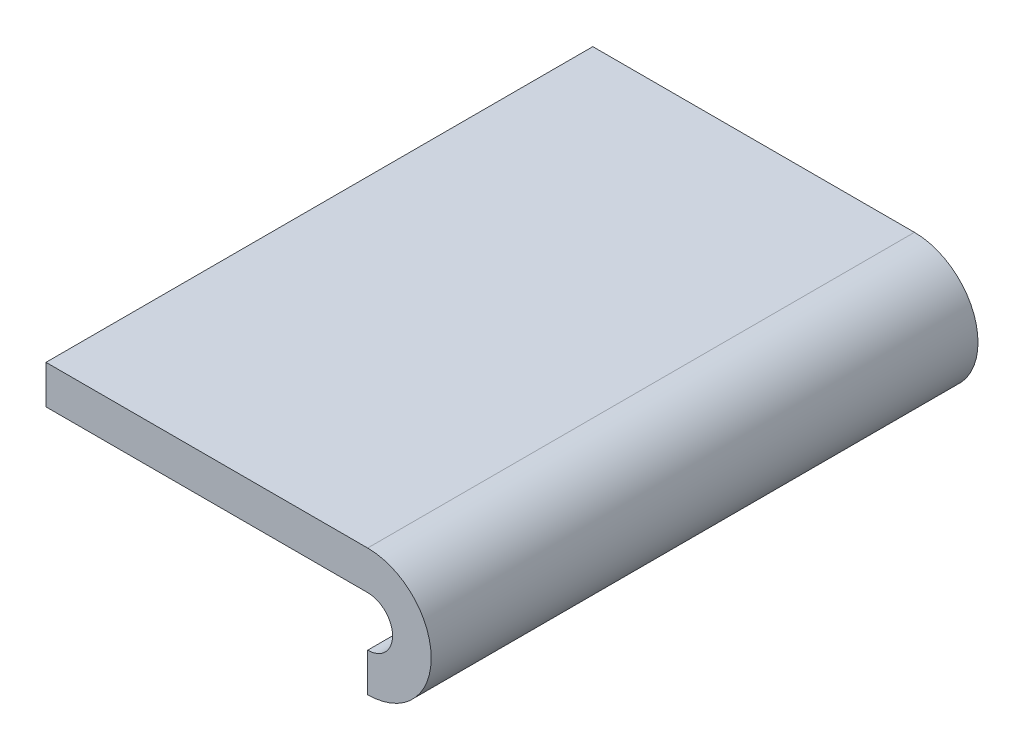
SolidWorks part; units mm, degrees
ref_plane "Front Plane" through (0, 0, 0) normal (0, 0, 1) x (1, 0, 0)
ref_plane "Top Plane" through (0, 0, 0) normal (0, 1, 0) x (1, 0, 0)
ref_plane "Right Plane" through (0, 0, 0) normal (1, 0, 0) x (0, 0, -1)
sketch "Sketch1" plane through (0, 0, 0) normal (0, 0, 1) x (1, 0, 0)
  line L0 (-100, 7.75) -> (0, 7.75)
  arc A0 (0, 7.75) -> (0, -7.75) centre (0, 0) cw
  dimension "D1" = 7.75
  dimension "D2" = 100
extrude "Extrude-Thin1" add sketch "Sketch1" along normal blind 170 thin thin type one direction reverse wall 12
